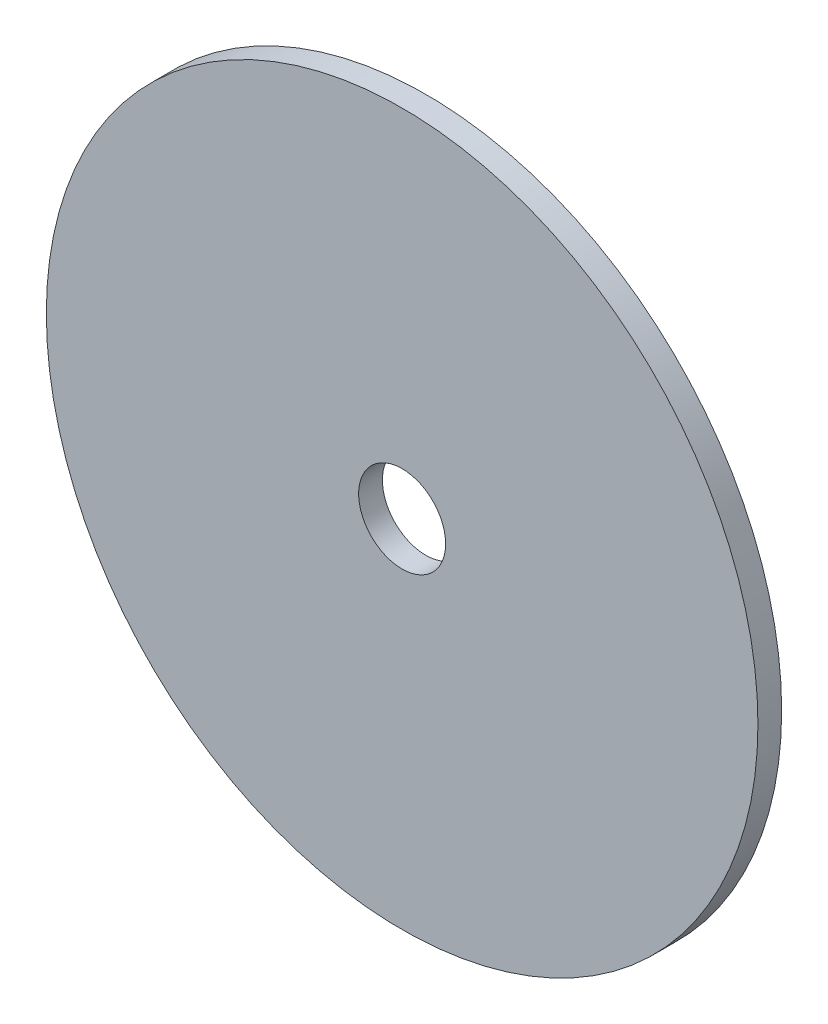
SolidWorks part; units mm, degrees
ref_plane "Спереди" through (0, 0, 0) normal (0, 0, 1) x (1, 0, 0)
ref_plane "Сверху" through (0, 0, 0) normal (0, 1, 0) x (1, 0, 0)
ref_plane "Справа" through (0, 0, 0) normal (1, 0, 0) x (0, 0, -1)
sketch "Эскиз1" plane through (0, 0, 0) normal (0, 0, 1) x (1, 0, 0)
  circle A0 centre (0, 0) radius 22.5
  circle A1 centre (0, 0) radius 2.75
  dimension "D1" = 5.5
  dimension "D2" = 45
extrude "Вытянуть1" add sketch "Эскиз1" along normal blind 1.5
